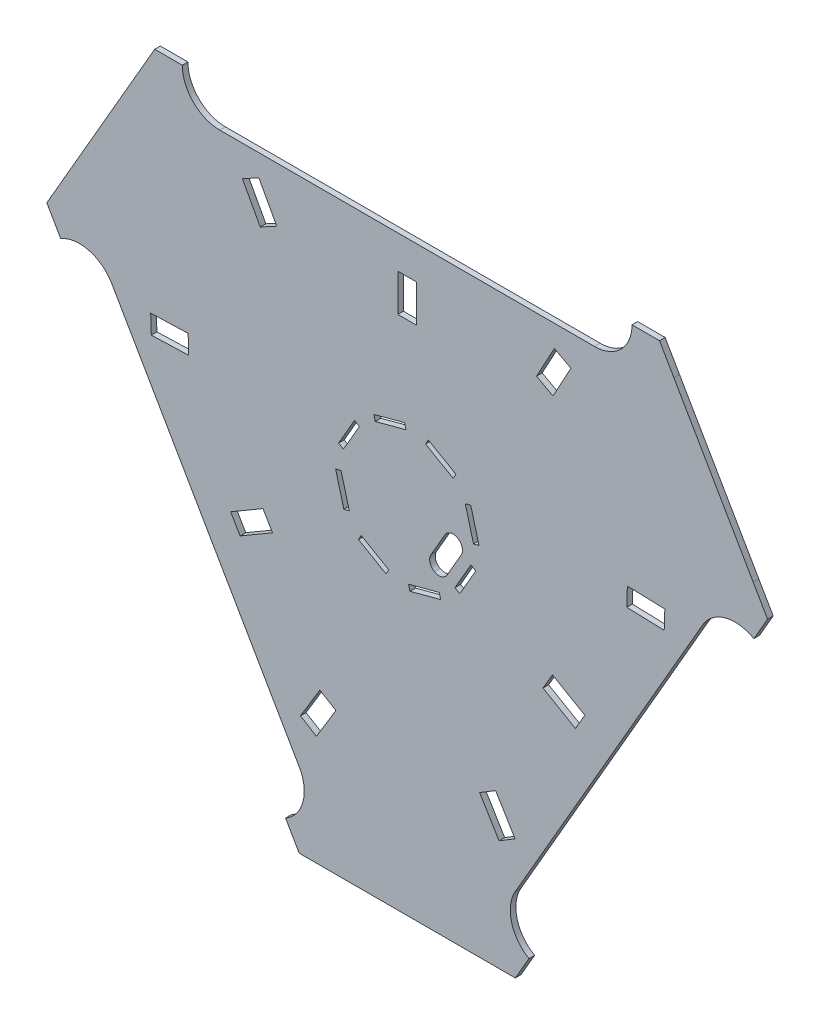
SolidWorks part; units mm, degrees
ref_plane "Plan de face" through (0, 0, 0) normal (0, 0, 1) x (1, 0, 0)
ref_plane "Plan de dessus" through (0, 0, 0) normal (0, 1, 0) x (1, 0, 0)
ref_plane "Plan de droite" through (0, 0, 0) normal (1, 0, 0) x (0, 0, -1)
sketch "Model" plane through (0, 0, 0) normal (0, 0, 1) x (1, 0, 0)
  line L662 (118.6164, -1154.7177) -> (127.9304, -1137.5509)
  line L663 (127.9304, -1137.5509) -> (136.72, -1142.3198)
  line L664 (136.72, -1142.3198) -> (127.5618, -1159.1996)
  line L665 (144.7752, -1191.5513) -> (166.7752, -1191.5513)
  line L666 (200.7752, -1152.8693) -> (200.7752, -1133.8449)
  line L667 (200.7752, -1133.8449) -> (210.7753, -1133.8449)
  line L668 (210.7753, -1133.8449) -> (210.7753, -1152.8693)
  line L669 (244.7753, -1191.5513) -> (266.7753, -1191.5513)
  line L670 (284.3929, -1158.9336) -> (275.3788, -1142.3198)
  line L671 (275.3788, -1142.3198) -> (284.1684, -1137.5509)
  line L672 (284.1684, -1137.5509) -> (293.3961, -1154.5585)
  line L673 (344.2368, -1185.0738) -> (354.3495, -1167.558)
  line L674 (354.3495, -1167.558) -> (328.3719, -1152.5598)
  line L675 (328.3719, -1152.5598) -> (333.1301, -1144.3183)
  line L676 (333.1301, -1144.3183) -> (264.2714, -1104.2143)
  line L677 (264.2714, -1104.2143) -> (284.3684, -1069.0978)
  line L678 (284.3684, -1069.0978) -> (353.3599, -1109.2793)
  line L679 (353.3599, -1109.2793) -> (358.3718, -1100.5983)
  line L680 (358.3718, -1100.5983) -> (384.3494, -1115.5964)
  line L681 (384.3494, -1115.5964) -> (394.4221, -1098.1497)
  line L682 (342.2811, -1068.5144) -> (322.6668, -1069.1396)
  line L683 (322.6668, -1069.1396) -> (322.3483, -1059.1447)
  line L684 (322.3483, -1059.1447) -> (341.8054, -1058.5245)
  line L685 (361.1808, -1027.8726) -> (350.1807, -1008.82)
  line L686 (299.413, -998.3554) -> (282.7063, -1008.1211)
  line L687 (282.7063, -1008.1211) -> (277.6598, -999.4879)
  line L688 (277.6598, -999.4879) -> (294.5118, -989.6372)
  line L689 (311.1809, -941.27) -> (300.1809, -922.2175)
  line L690 (262.3971, -922.8937) -> (252.3743, -939.4373)
  line L691 (252.3743, -939.4373) -> (243.8215, -934.2556)
  line L692 (243.8215, -934.2556) -> (254.1849, -917.15)
  line L693 (254.1849, -917.15) -> (254.439, -917.3039)
  line L694 (255.6733, -858.5099) -> (247.9625, -858.5099)
  line L695 (247.9625, -858.5099) -> (235.7176, -858.5099)
  line L696 (235.7176, -858.5099) -> (235.7176, -888.5099)
  line L697 (235.7176, -888.5099) -> (225.7175, -888.5099)
  line L698 (225.7175, -888.5099) -> (225.7175, -968.5099)
  line L699 (225.7175, -968.5099) -> (185.7176, -968.5099)
  line L700 (185.7176, -968.5099) -> (185.7176, -888.5099)
  line L701 (185.7176, -888.5099) -> (175.7175, -888.5099)
  line L702 (175.7175, -888.5099) -> (175.7175, -858.5099)
  line L703 (175.7175, -858.5099) -> (163.4726, -858.5099)
  line L704 (163.4726, -858.5099) -> (155.7618, -858.5099)
  line L705 (156.5681, -917.6896) -> (156.7309, -917.591)
  line L706 (156.7309, -917.591) -> (167.0942, -934.6965)
  line L707 (167.0942, -934.6965) -> (158.5415, -939.8782)
  line L708 (158.5415, -939.8782) -> (148.4396, -923.2044)
  line L709 (111.2542, -922.2175) -> (100.2542, -941.27)
  line L710 (116.676, -990.2373) -> (133.2558, -999.9289)
  line L711 (133.2558, -999.9289) -> (128.2093, -1008.5621)
  line L712 (128.2093, -1008.5621) -> (111.6322, -998.8721)
  line L713 (61.2542, -1008.82) -> (50.2542, -1027.8726)
  line L714 (69.6666, -1058.9832) -> (88.5674, -1059.5857)
  line L715 (88.5674, -1059.5857) -> (88.2488, -1069.5806)
  line L716 (88.2488, -1069.5806) -> (69.0689, -1068.9692)
  line L717 (17.2057, -1098.2221) -> (21.0894, -1104.9488)
  line L718 (21.0894, -1104.9488) -> (27.2432, -1115.6074)
  line L719 (27.2432, -1115.6074) -> (53.2397, -1100.5983)
  line L720 (53.2397, -1100.5983) -> (58.2396, -1109.2586)
  line L721 (58.2396, -1109.2586) -> (127.5216, -1069.2586)
  line L722 (127.5216, -1069.2586) -> (147.5216, -1103.8996)
  line L723 (147.5216, -1103.8996) -> (78.2396, -1143.8996)
  line L724 (78.2396, -1143.8996) -> (83.2396, -1152.5598)
  line L725 (83.2396, -1152.5598) -> (57.2432, -1167.5689)
  line L726 (57.2432, -1167.5689) -> (63.4324, -1178.2888)
  line L727 (63.4324, -1178.2888) -> (63.4324, -1178.289)
  line L728 (63.4324, -1178.289) -> (67.3217, -1185.0257)
  line L729 (347.5042, -990.9847) -> (447.5042, -1164.1898)
  line L730 (440.1849, -1191.5058) -> (447.4682, -1204.1207)
  line L731 (447.4682, -1204.1207) -> (462.9049, -1204.1207)
  line L732 (462.9049, -1204.1207) -> (547.3949, -1204.1207)
  line L733 (547.3949, -1204.1207) -> (562.8317, -1204.1207)
  line L734 (562.8317, -1204.1207) -> (570.1149, -1191.5058)
  line L735 (562.7957, -1164.1898) -> (662.7956, -990.9847)
  line L736 (690.1116, -983.6655) -> (697.4457, -970.9625)
  line L737 (697.4457, -970.9625) -> (689.7781, -957.6819)
  line L738 (689.7781, -957.6819) -> (647.4351, -884.3418)
  line L739 (647.4351, -884.3418) -> (647.4351, -884.3416)
  line L740 (647.4351, -884.3416) -> (639.7782, -871.0793)
  line L741 (639.7782, -871.0793) -> (625.0923, -871.0793)
  line L742 (605.0923, -891.0793) -> (405.0923, -891.0793)
  line L743 (385.0923, -871.0793) -> (370.3705, -871.0793)
  line L744 (370.3705, -871.0793) -> (312.7787, -970.8316)
  line L745 (312.7787, -970.8316) -> (320.1882, -983.6655)
  line L1029 (622.6187, -993.0501) -> (642.6085, -993.6872)
  line L1030 (642.6085, -993.6872) -> (642.29, -1003.6822)
  line L1031 (642.29, -1003.6822) -> (622.3, -1003.045)
  line L1032 (622.3, -1003.045) -> (622.6187, -993.0501)
  line L1033 (594.8781, -1072.7947) -> (577.6116, -1062.7018)
  line L1034 (577.6116, -1062.7018) -> (582.6582, -1054.0686)
  line L1035 (582.6582, -1054.0686) -> (599.9247, -1064.1615)
  line L1036 (599.9247, -1064.1615) -> (594.8781, -1072.7947)
  line L1037 (583.6852, -902.7316) -> (592.4748, -907.5005)
  line L1038 (592.4748, -907.5005) -> (582.9371, -925.0797)
  line L1039 (582.9371, -925.0797) -> (574.1474, -920.3108)
  line L1040 (574.1474, -920.3108) -> (583.6852, -902.7316)
  line L1041 (552.326, -1122.7524) -> (562.6894, -1139.858)
  line L1042 (562.6894, -1139.858) -> (554.1366, -1145.0397)
  line L1043 (554.1366, -1145.0397) -> (543.7732, -1127.9341)
  line L1044 (543.7732, -1127.9341) -> (552.326, -1122.7524)
  line L1045 (500.0922, -908.7858) -> (510.0922, -908.7858)
  line L1046 (510.0922, -908.7858) -> (510.0922, -928.7858)
  line L1047 (510.0922, -928.7858) -> (500.0922, -928.7858)
  line L1048 (500.0922, -928.7858) -> (500.0922, -908.7858)
  line L1049 (458.4931, -1123.1934) -> (467.0459, -1128.3751)
  line L1050 (467.0459, -1128.3751) -> (456.6826, -1145.4807)
  line L1051 (456.6826, -1145.4807) -> (448.1298, -1140.299)
  line L1052 (448.1298, -1140.299) -> (458.4931, -1123.1934)
  line L1053 (425.9509, -902.7316) -> (435.4887, -920.3108)
  line L1054 (435.4887, -920.3108) -> (426.6991, -925.0797)
  line L1055 (426.6991, -925.0797) -> (417.1613, -907.5005)
  line L1056 (417.1613, -907.5005) -> (425.9509, -902.7316)
  line L1057 (428.1611, -1054.5095) -> (433.2077, -1063.1428)
  line L1058 (433.2077, -1063.1428) -> (415.9412, -1073.2357)
  line L1059 (415.9412, -1073.2357) -> (410.8947, -1064.6025)
  line L1060 (410.8947, -1064.6025) -> (428.1611, -1054.5095)
  line L1061 (388.2006, -993.4911) -> (388.5191, -1003.486)
  line L1062 (388.5191, -1003.486) -> (368.5293, -1004.1231)
  line L1063 (368.5293, -1004.1231) -> (368.2108, -994.1282)
  line L1064 (368.2108, -994.1282) -> (388.2006, -993.4911)
  spline S707 degree 3 poles (67.3217, -1185.0257) (70.4273, -1166.5936) (86.4601, -1152.5513) (105.7752, -1152.5513) knots 0 0 0 0 1 1 1 1
  spline S708 degree 3 poles (105.7752, -1152.5513) (110.2746, -1152.5513) (114.595, -1153.3158) (118.6164, -1154.7177) knots 1 1 1 1 2 2 2 2
  spline S709 degree 3 poles (127.5618, -1159.1996) (137.9463, -1166.2065) (144.7752, -1178.0813) (144.7752, -1191.5513) knots 5 5 5 5 6 6 6 6
  spline S710 degree 3 poles (166.7752, -1191.5513) (166.7752, -1171.7063) (181.5976, -1155.3237) (200.7752, -1152.8693) knots 7 7 7 7 8 8 8 8
  spline S711 degree 3 poles (210.7753, -1152.8693) (229.9529, -1155.3237) (244.7753, -1171.7063) (244.7753, -1191.5513) knots 11 11 11 11 12 12 12 12
  spline S712 degree 3 poles (266.7753, -1191.5513) (266.7753, -1177.9081) (273.7825, -1165.9033) (284.3929, -1158.9336) knots 13 13 13 13 14 14 14 14
  spline S713 degree 3 poles (293.3961, -1154.5585) (297.2856, -1153.2575) (301.4478, -1152.5513) (305.7752, -1152.5513) knots 17 17 17 17 18 18 18 18
  spline S714 degree 3 poles (305.7752, -1152.5513) (325.1072, -1152.5513) (341.151, -1166.6181) (344.2368, -1185.0738) knots 18 18 18 18 19 19 19 19
  spline S715 degree 3 poles (394.4221, -1098.1497) (376.8685, -1104.7819) (356.594, -1097.9278) (346.9058, -1081.1476) knots 28 28 28 28 29 29 29 29
  spline S716 degree 3 poles (346.9058, -1081.1476) (344.5792, -1077.1177) (343.0553, -1072.8451) (342.2811, -1068.5144) knots 29 29 29 29 30 30 30 30
  spline S717 degree 3 poles (341.8054, -1058.5245) (342.8076, -1046.187) (349.6499, -1034.53) (361.1808, -1027.8726) knots 33 33 33 33 34 34 34 34
  spline S718 degree 3 poles (350.1807, -1008.82) (332.8616, -1018.8192) (311.0631, -1014.0226) (299.413, -998.3554) knots 35 35 35 35 36 36 36 36
  spline S719 degree 3 poles (294.5118, -989.6372) (287.327, -971.8923) (294.1287, -951.1151) (311.1809, -941.27) knots 39 39 39 39 40 40 40 40
  spline S720 degree 3 poles (300.1809, -922.2175) (288.1117, -929.1856) (273.8672, -928.9671) (262.3971, -922.8937) knots 43 43 43 43 44 44 44 44
  spline S721 degree 3 poles (254.439, -917.3039) (251.5315, -914.6591) (248.9762, -911.5284) (246.9059, -907.9425) knots 48 48 48 48 49 49 49 49
  spline S722 degree 3 poles (246.9059, -907.9425) (237.277, -891.265) (241.3676, -870.4333) (255.6733, -858.5099) knots 49 49 49 49 50 50 50 50
  spline S723 degree 3 poles (155.7618, -858.5099) (170.0675, -870.4333) (174.1581, -891.265) (164.5292, -907.9425) knots 61 61 61 61 62 62 62 62
  spline S724 degree 3 poles (164.5292, -907.9425) (162.3578, -911.7037) (159.6535, -914.9655) (156.5681, -917.6896) knots 62 62 62 62 63 63 63 63
  spline S725 degree 3 poles (148.4396, -923.2044) (137.0752, -928.9728) (123.1145, -929.0649) (111.2542, -922.2175) knots 67 67 67 67 68 68 68 68
  spline S726 degree 3 poles (100.2542, -941.27) (117.499, -951.2262) (124.2617, -972.3631) (116.676, -990.2373) knots 71 71 71 71 72 72 72 72
  spline S727 degree 3 poles (111.6322, -998.8721) (99.8908, -1014.1275) (78.3818, -1018.7086) (61.2542, -1008.82) knots 75 75 75 75 76 76 76 76
  spline S728 degree 3 poles (50.2542, -1027.8726) (61.9282, -1034.6125) (68.7988, -1046.4764) (69.6666, -1058.9832) knots 79 79 79 79 80 80 80 80
  spline S729 degree 3 poles (69.0689, -1068.9692) (68.271, -1073.1441) (66.7744, -1077.2589) (64.5293, -1081.1476) knots 83 83 83 83 84 84 84 84
  spline S730 degree 3 poles (64.5293, -1081.1476) (54.8766, -1097.8664) (34.7149, -1104.7317) (17.2057, -1098.2221) knots 84 84 84 84 85 85 85 85
  spline S731 degree 3 poles (345.1602, -1171.4403) (344.2035, -1170.888) (343.8759, -1169.6648) (344.4281, -1168.7083) knots 3 3 3 3 4 4 4 4
  spline S732 degree 3 poles (347.8922, -1170.7082) (347.3399, -1171.6649) (346.1167, -1171.9926) (345.1602, -1171.4403) knots 2 2 2 2 3 3 3 3
  spline S733 degree 3 poles (347.1603, -1167.9762) (348.1168, -1168.5285) (348.4446, -1169.7517) (347.8922, -1170.7082) knots 1 1 1 1 2 2 2 2
  spline S734 degree 3 poles (344.4281, -1168.7083) (344.9804, -1167.7517) (346.2036, -1167.4239) (347.1603, -1167.9762) knots 0 0 0 0 1 1 1 1
  spline S735 degree 3 poles (381.117, -1109.1613) (380.1603, -1108.609) (379.8327, -1107.3858) (380.3849, -1106.4292) knots 3 3 3 3 4 4 4 4
  spline S736 degree 3 poles (383.849, -1108.4293) (383.2967, -1109.3858) (382.0735, -1109.7136) (381.117, -1109.1613) knots 2 2 2 2 3 3 3 3
  spline S737 degree 3 poles (383.1169, -1105.6972) (384.0736, -1106.2495) (384.4012, -1107.4727) (383.849, -1108.4293) knots 1 1 1 1 2 2 2 2
  spline S738 degree 3 poles (380.3849, -1106.4292) (380.9372, -1105.4727) (382.1604, -1105.1449) (383.1169, -1105.6972) knots 0 0 0 0 1 1 1 1
  spline S739 degree 3 poles (241.6744, -866.5305) (240.5699, -866.5305) (239.6743, -865.6351) (239.6743, -864.5305) (239.6743, -863.426) (240.5699, -862.5305) (241.6744, -862.5305) knots 2 2 2 2 3 3 3 4 4 4 4
  spline S740 degree 3 poles (241.6744, -862.5305) (242.7789, -862.5305) (243.6744, -863.426) (243.6744, -864.5305) (243.6744, -865.6351) (242.7789, -866.5305) (241.6744, -866.5305) knots 0 0 0 0 1 1 1 2 2 2 2
  spline S741 degree 3 poles (171.7608, -864.5305) (171.7608, -865.6351) (170.8653, -866.5305) (169.7608, -866.5305) (168.6563, -866.5305) (167.7607, -865.6351) (167.7607, -864.5305) knots 2 2 2 2 3 3 3 4 4 4 4
  spline S742 degree 3 poles (167.7607, -864.5305) (167.7607, -863.426) (168.6563, -862.5305) (169.7608, -862.5305) (170.8653, -862.5305) (171.7608, -863.426) (171.7608, -864.5305) knots 0 0 0 0 1 1 1 2 2 2 2
  spline S743 degree 3 poles (31.2266, -1106.4292) (31.7788, -1107.3858) (31.4512, -1108.609) (30.4945, -1109.1613) knots 3 3 3 3 4 4 4 4
  spline S744 degree 3 poles (28.4944, -1105.6972) (29.4511, -1105.1449) (30.6743, -1105.4727) (31.2266, -1106.4292) knots 2 2 2 2 3 3 3 3
  spline S745 degree 3 poles (27.7625, -1108.4293) (27.2101, -1107.4727) (27.5379, -1106.2495) (28.4944, -1105.6972) knots 1 1 1 1 2 2 2 2
  spline S746 degree 3 poles (30.4945, -1109.1613) (29.538, -1109.7136) (28.3148, -1109.3858) (27.7625, -1108.4293) knots 0 0 0 0 1 1 1 1
  spline S747 degree 3 poles (63.7193, -1170.7082) (63.1669, -1169.7517) (63.4947, -1168.5285) (64.4512, -1167.9762) knots 3 3 3 3 4 4 4 4
  spline S748 degree 3 poles (66.4513, -1171.4403) (65.4948, -1171.9926) (64.2716, -1171.6649) (63.7193, -1170.7082) knots 2 2 2 2 3 3 3 3
  spline S749 degree 3 poles (67.1834, -1168.7083) (67.7356, -1169.6648) (67.4078, -1170.888) (66.4513, -1171.4403) knots 1 1 1 1 2 2 2 2
  spline S750 degree 3 poles (64.4512, -1167.9762) (65.4079, -1167.4239) (66.6311, -1167.7517) (67.1834, -1168.7083) knots 0 0 0 0 1 1 1 1
  spline S751 degree 3 poles (447.5042, -1164.1898) (453.0261, -1173.7541) (449.7492, -1185.9838) (440.1849, -1191.5058) knots 1 1 1 1 2 2 2 2
  spline S752 degree 3 poles (570.1149, -1191.5058) (560.5507, -1185.9838) (557.2737, -1173.7541) (562.7957, -1164.1898) knots 7 7 7 7 8 8 8 8
  spline S753 degree 3 poles (662.7956, -990.9847) (668.3175, -981.4205) (680.5473, -978.1436) (690.1116, -983.6655) knots 9 9 9 9 10 10 10 10
  spline S754 degree 3 poles (625.0923, -871.0793) (625.0923, -882.125) (616.138, -891.0793) (605.0923, -891.0793) knots 17 17 17 17 18 18 18 18
  spline S755 degree 3 poles (405.0923, -891.0793) (394.0466, -891.0793) (385.0923, -882.125) (385.0923, -871.0793) knots 19 19 19 19 20 20 20 20
  spline S756 degree 3 poles (320.1882, -983.6655) (329.7525, -978.1435) (341.9823, -981.4205) (347.5042, -990.9847) knots 23 23 23 23 24 24 24 24
extrude "Boss.-Extru.1" add sketch "Model" along normal blind 3 contours L745 S756 L729 S751 L730 L731 L732 L733 L734 S752 L735 S753 L736 L737 L738 L739 L740 L741 S754 L742 S755 L743 L744 L1063 L1064 L1061 L1062 L1059 L1060 L1057 L1058 L1055 L1056 L1053 L1054 L1051 L1052 L1049 L1050 L1047 L1048 L1045 L1046 L1043 L1044
sketch "Esquisse2" plane through (0, 0, 0) normal (0, 0, -1) x (-1, 0, 0)
  line L1 (-428.1611, -1054.5095) -> (-433.2077, -1063.1428) construction
  line L2 (-430.6844, -1058.8262) -> (-889.9356, -790.3715) construction
  line L4 (-505.0922, -928.7858) -> (-505.0922, -1231.2353) construction
  line L5 (-510.0922, -928.7858) -> (-500.0922, -928.7858) construction
  line L7 (-534.8399, -1032.4656) -> (-475.3445, -998.1968) construction
  line L9 (-562.7957, -1164.1898) -> (-662.7956, -990.9847) construction
  point P4 (-505.0922, -1015.3312)
  point P9 (-465.1643, -754.2147)
  point P12 (-505.0922, -1015.3312)
  line B0 (-526.4343, -1036.035) -> (-533.9343, -1023.0447)
  line B1 (-525.2741, -1018.0447) -> (-517.7741, -1031.035)
  line B2 (-466.9122, -1016.8381) -> (-471.312, -1033.259)
  line B3 (-471.312, -1033.259) -> (-474.2096, -1032.4828)
  line B4 (-474.2096, -1032.4828) -> (-469.8095, -1016.0617)
  line B5 (-469.8095, -1016.0617) -> (-466.9122, -1016.8381)
  line B6 (-505.7842, -1050.635) -> (-522.205, -1046.2349)
  line B7 (-522.205, -1046.2349) -> (-522.9816, -1049.1324)
  line B8 (-522.9816, -1049.1324) -> (-506.5608, -1053.5325)
  line B9 (-506.5608, -1053.5325) -> (-505.7842, -1050.635)
  line B10 (-543.4146, -1013.888) -> (-540.517, -1014.6642)
  line B11 (-540.517, -1014.6642) -> (-536.1171, -998.2433)
  line B12 (-536.1171, -998.2433) -> (-539.0147, -997.4671)
  line B13 (-539.0147, -997.4671) -> (-543.4146, -1013.888)
  line B14 (-487.2871, -981.3997) -> (-503.7081, -976.9997)
  line B15 (-503.7081, -976.9997) -> (-504.4842, -979.8981)
  line B16 (-504.4842, -979.8981) -> (-488.0643, -984.2975)
  line B17 (-488.0643, -984.2975) -> (-487.2871, -981.3997)
  line B18 (-539.0899, -1025.1044) -> (-530.5899, -1039.8268)
  line B19 (-530.5899, -1039.8268) -> (-533.188, -1041.3268)
  line B20 (-533.188, -1041.3268) -> (-541.688, -1026.6044)
  line B21 (-541.688, -1026.6044) -> (-539.0899, -1025.1044)
  line B22 (-516.4257, -978.6634) -> (-514.9257, -981.2615)
  line B23 (-514.9257, -981.2615) -> (-529.6482, -989.7615)
  line B24 (-529.6482, -989.7615) -> (-531.1482, -987.1634)
  line B25 (-531.1482, -987.1634) -> (-516.4257, -978.6634)
  line B26 (-479.0952, -1043.3194) -> (-480.5952, -1040.7213)
  line B27 (-480.5952, -1040.7213) -> (-495.3177, -1049.2213)
  line B28 (-495.3177, -1049.2213) -> (-493.8176, -1051.8194)
  line B29 (-493.8176, -1051.8194) -> (-479.0952, -1043.3194)
  line B30 (-476.9964, -989.3356) -> (-468.4964, -1004.058)
  line B31 (-468.4964, -1004.058) -> (-471.0945, -1005.558)
  line B32 (-471.0945, -1005.558) -> (-479.5945, -990.8356)
  line B33 (-479.5945, -990.8356) -> (-476.9964, -989.3356)
  spline B34 degree 3 poles (-533.9343, -1023.0447) (-535.315, -1020.6532) (-534.4957, -1017.5952) (-532.1042, -1016.2145) knots 1 1 1 1 2 2 2 2
  spline B35 degree 3 poles (-532.1042, -1016.2145) (-529.7127, -1014.8338) (-526.6548, -1015.6532) (-525.2741, -1018.0447) knots 2 2 2 2 3 3 3 3
  spline B36 degree 3 poles (-517.7741, -1031.035) (-516.3934, -1033.4265) (-517.2127, -1036.4845) (-519.6042, -1037.8652) knots 4 4 4 4 5 5 5 5
  spline B37 degree 3 poles (-519.6042, -1037.8652) (-521.9957, -1039.2459) (-525.0536, -1038.4265) (-526.4343, -1036.035) knots 5 5 5 5 6 6 6 6
sketch_block_instance "Bloc1-1"
sketch_block "Bloc1"
extrude "Enlèv. mat.-Extru.2" cut sketch "Esquisse2" against normal through all
